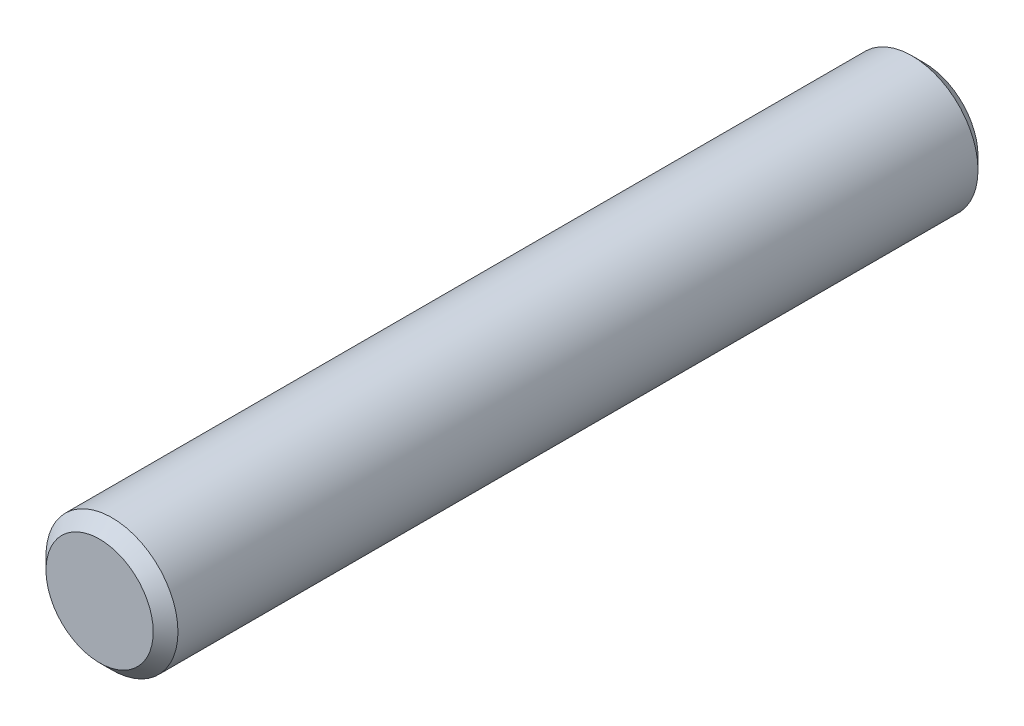
SolidWorks part; units mm, degrees
ref_plane "Ön Düzlem" through (0, 0, 0) normal (0, 0, 1) x (1, 0, 0)
ref_plane "Üst Düzlem" through (0, 0, 0) normal (0, 1, 0) x (1, 0, 0)
ref_plane "Sağ Düzlem" through (0, 0, 0) normal (1, 0, 0) x (0, 0, -1)
sketch "Sketch1" plane through (0, 0, 0) normal (0, 0, 1) x (1, 0, 0)
  circle A0 centre (0, 0) radius 4
  dimension "D1" = 8
extrude "Boss-Extrude1" add sketch "Sketch1" along normal blind 50
chamfer "Chamfer1" distance 0.75 angle 45 2 edges at (4, 0, 0) (4, 0, 50)
